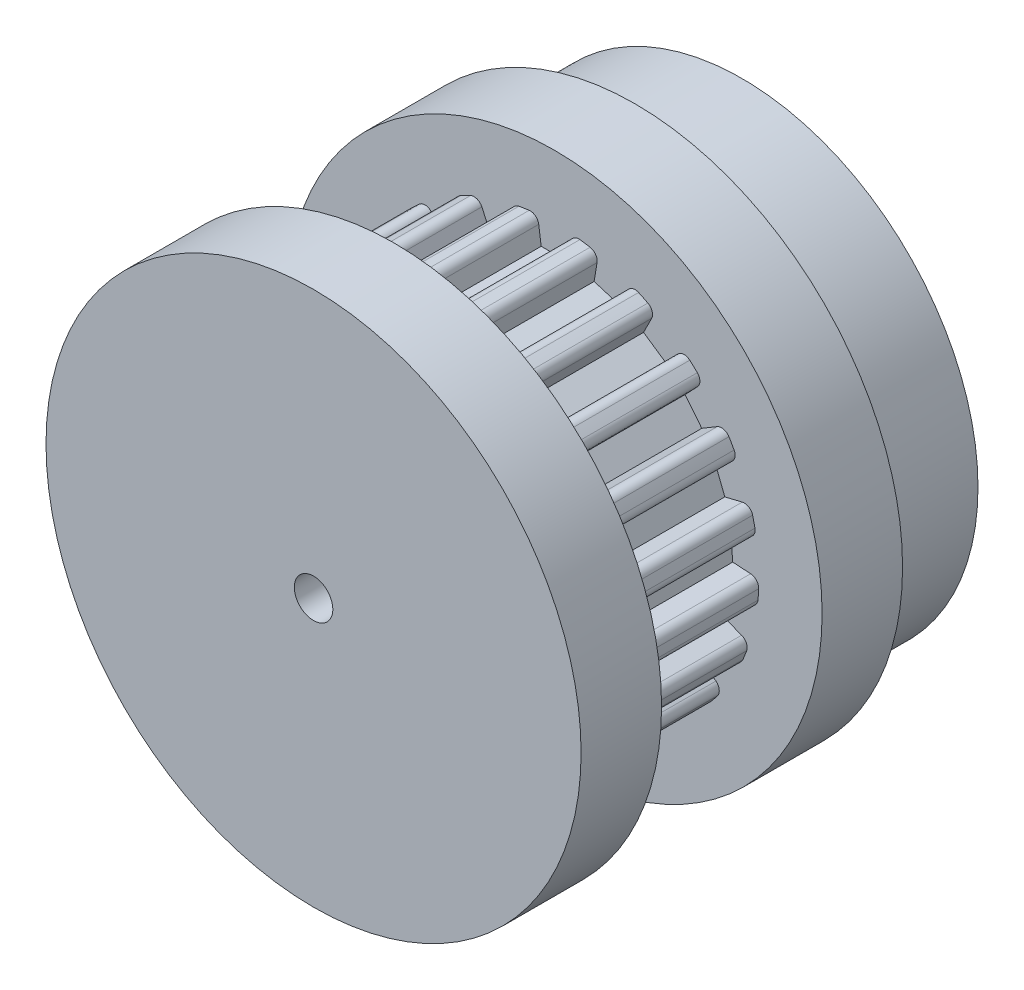
SolidWorks part; units mm, degrees
ref_plane "Front Plane" through (0, 0, 0) normal (0, 0, 1) x (1, 0, 0)
ref_plane "Top Plane" through (0, 0, 0) normal (0, 1, 0) x (1, 0, 0)
ref_plane "Right Plane" through (0, 0, 0) normal (1, 0, 0) x (0, 0, -1)
sketch "Sketch3" plane through (0, 0, 0) normal (0, 0, 1) x (1, 0, 0)
  circle A0 centre (0, 0) radius 12.1285
  dimension "D1" = 24.257
extrude "Boss-Extrude1" add sketch "Sketch3" along normal blind 9.525 contours A0
sketch "Sketch4" plane through (0, 0, 0) normal (0, 0, -1) x (-1, 0, 0)
  line L0 (-1.5875, 16.3688) -> (1.5875, 16.3688)
  line L1 (1.5875, 16.3688) -> (0.7937, 10.541)
  line L2 (0.7937, 10.541) -> (-0.7937, 10.541)
  line L3 (-0.7937, 10.541) -> (-1.5875, 16.3688)
  circle A0 centre (0, 0) radius 12.1285 construction
  point P2 (0, 10.541)
  point P6 (0, 12.1285)
  circle M5 centre (0, 0) radius 12.1285
  dimension "D1" = 3.175
  dimension "D2" = 1.5875
  dimension "D3" = 1.5875
  dimension "D4" = 5.8278
extrude "Cut-Extrude1" cut sketch "Sketch4" against normal blind 9.525 contours L3 L1 L0 M5
fillet "Fillet1" radius 0.508 1 edges at (1.0043, 12.0868, 4.7625)
fillet "Fillet2" radius 0.508 1 edges at (-1.0043, 12.0868, 4.7625)
sketch "Sketch5" plane through (0, 0, 9.525) normal (0, 0, 1) x (1, 0, 0)
  circle A0 centre (0, 0) radius 15.875
  dimension "D1" = 31.75
extrude "Boss-Extrude2" add sketch "Sketch5" along normal blind 4.7752
pattern_circular "CirPattern1" count 21 over 360 about axis through (0, 0, 0) along (0, 0, 1) of "Cut-Extrude1", "Fillet1", "Fillet2"
sketch "Sketch7" plane through (0, 0, 0) normal (0, 0, -1) x (-1, 0, 0)
  circle A0 centre (0, 0) radius 15.875
  dimension "D1" = 31.75
extrude "Boss-Extrude3" add sketch "Sketch7" along normal blind 4.7752
sketch "Sketch8" plane through (0, 0, -4.7752) normal (0, 0, -1) x (-1, 0, 0)
  circle A0 centre (0, 0) radius 14
  dimension "D1" = 28
extrude "Boss-Extrude6" add sketch "Sketch8" along normal blind 6.35
sketch "Sketch14" plane through (0, 0, -11.1252) normal (0, 0, -1) x (-1, 0, 0)
  circle A0 centre (0, 0) radius 1.143
  dimension "D1" = 2.286
extrude "Cut-Extrude5" cut sketch "Sketch14" against normal through all
sketch "Sketch15" plane through (0, 0, 0) normal (0, 1, 0) x (1, 0, 0)
  line L0 (0, 11.1252) -> (0, 4.7752) construction
  line L1 (14, 11.1252) -> (-14, 11.1252) construction
  line L2 (15.875, 4.7752) -> (-15.875, 4.7752) construction
  circle A0 centre (0, 7.9502) radius 1.5
  point P8 (0, 0)
  point P9 (0, 7.9502)
  dimension "D1" = 3
extrude "Cut-Extrude6" cut sketch "Sketch15" against normal through all
